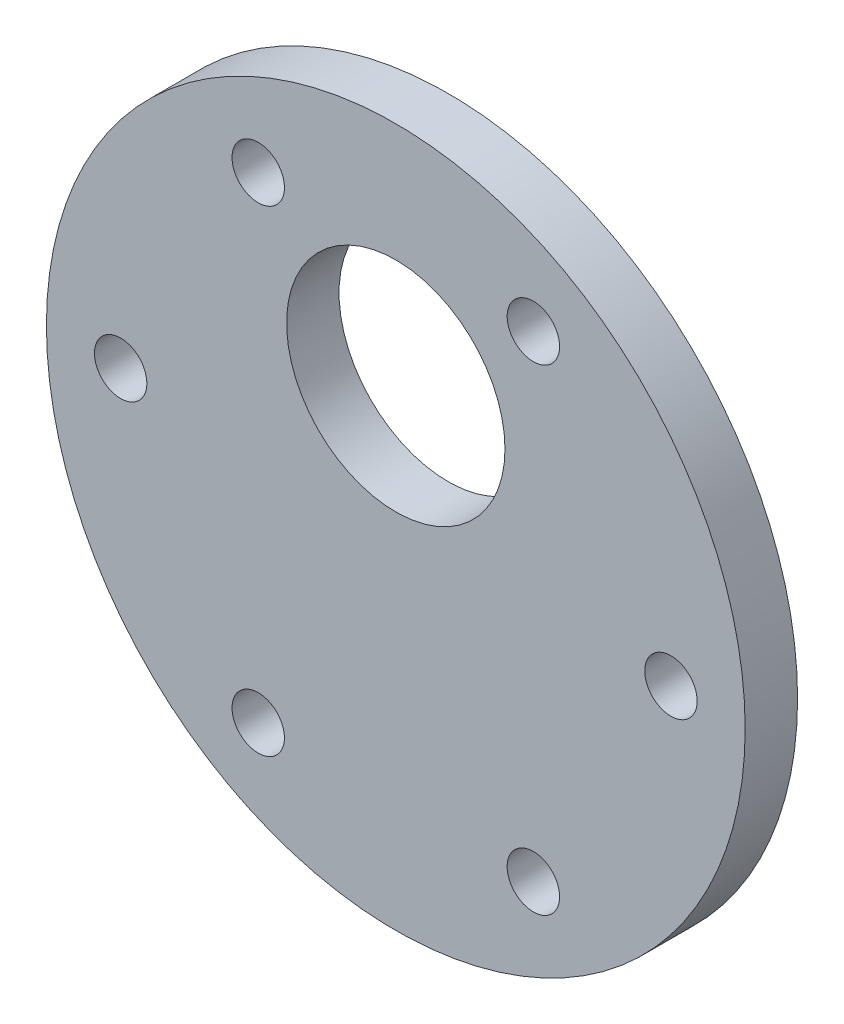
SolidWorks part; units mm, degrees
material "Acrylic (Medium-high impact)"
ref_plane "Front Plane" through (0, 0, 0) normal (0, 0, 1) x (1, 0, 0)
ref_plane "Top Plane" through (0, 0, 0) normal (0, 1, 0) x (1, 0, 0)
ref_plane "Right Plane" through (0, 0, 0) normal (1, 0, 0) x (0, 0, -1)
sketch "Sketch3" plane through (0, 0, 0) normal (0, 0, 1) x (1, 0, 0)
  circle A0 centre (0, 0) radius 20
  dimension "D1" = 40
extrude "Boss-Extrude1" add sketch "Sketch3" along normal blind 3
sketch "Sketch2" plane through (0, 0, 0) normal (0, 0, 1) x (1, 0, 0)
  line L1 (0, 0) -> (-15.75, 0) construction
  circle A0 centre (-15.75, 0) radius 1.5
  circle A1 centre (-7.875, 13.6399) radius 1.5
  circle A2 centre (7.875, 13.6399) radius 1.5
  circle A3 centre (15.75, 0) radius 1.5
  circle A4 centre (7.875, -13.6399) radius 1.5
  circle A5 centre (-7.875, -13.6399) radius 1.5
  circle A6 centre (0, 7) radius 6.25
  point P0 (0, 0)
  dimension "D2" = 3
  dimension "D6" = 7
  dimension "D3" = 12.5
  dimension "D5" = 15.75
  dimension "D4" = 6
extrude "Cut-Extrude2" cut sketch "Sketch2" against normal through all and the other way through all
